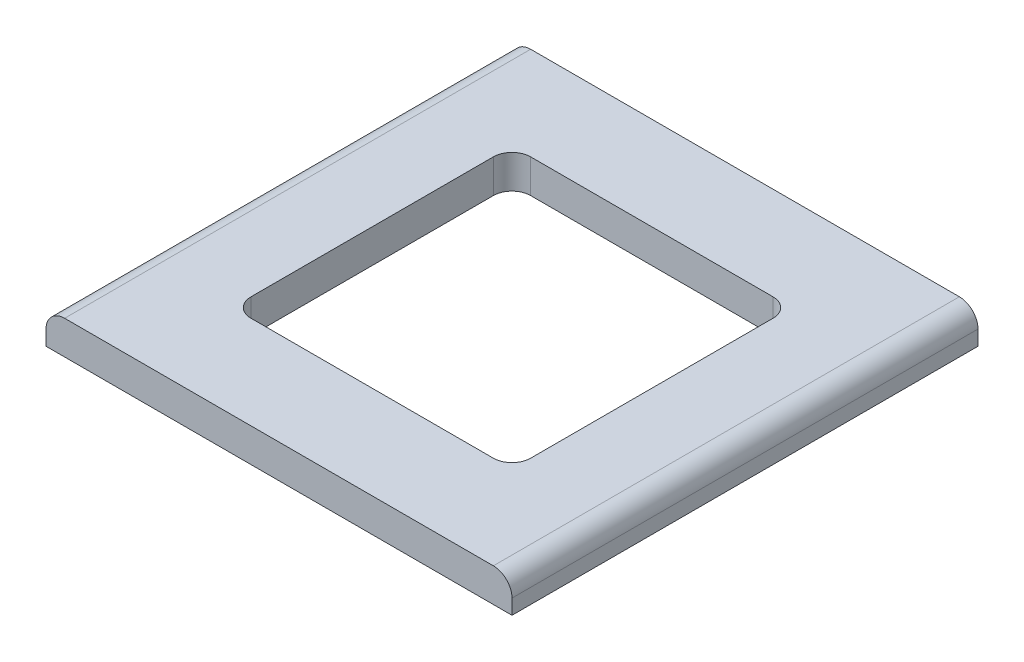
SolidWorks part; units mm, degrees
ref_plane "前视基准面" through (0, 0, 0) normal (0, 0, 1) x (1, 0, 0)
ref_plane "上视基准面" through (0, 0, 0) normal (0, 1, 0) x (1, 0, 0)
ref_plane "右视基准面" through (0, 0, 0) normal (1, 0, 0) x (0, 0, -1)
other "Configuration Table"
sketch "草图1" plane through (0, 0, 0) normal (0, 1, 0) x (1, 0, 0)
  line L1 (-125, -125) -> (125, -125)
  line L2 (-125, -125) -> (-125, 125)
  line L3 (-125, 125) -> (125, 125)
  line L4 (125, -125) -> (125, 125)
  line L5 (-75, 75) -> (75, 75)
  line L6 (-75, 75) -> (-75, -75)
  line L7 (-75, -75) -> (75, -75)
  line L8 (75, 75) -> (75, -75)
  point P4 (-125, 0)
  point P6 (0, 125)
  point P11 (0, 75)
  point P12 (-75, 0)
  dimension "D3" = 150
  dimension "D4" = 150
  dimension "D1" = 250
  dimension "D2" = 250
extrude "凸台-拉伸1" add sketch "草图1" along normal blind 18
fillet "圆角1" radius 10 2 edges at (-125, 18, 0) (125, 18, 0)
fillet "圆角2" radius 10 4 edges at (75, 9, 75) (-75, 9, 75) (75, 9, -75) (-75, 9, -75)
